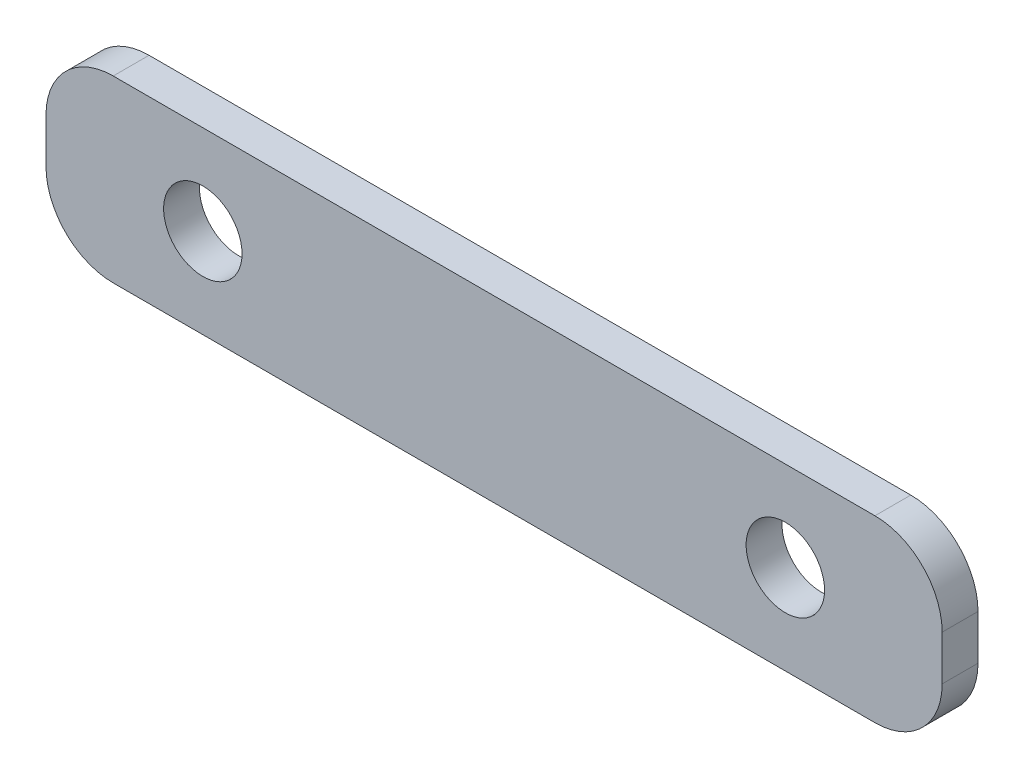
SolidWorks part; units mm, degrees
ref_plane "Plano frontal" through (0, 0, 0) normal (0, 0, 1) x (1, 0, 0)
ref_plane "Plano superior" through (0, 0, 0) normal (0, 1, 0) x (1, 0, 0)
ref_plane "Plano direito" through (0, 0, 0) normal (1, 0, 0) x (0, 0, -1)
sketch "Esboço1" plane through (0, 0, 0) normal (0, 0, 1) x (1, 0, 0)
  line L0 (0, 0) -> (0, 40)
  line L1 (0, 40) -> (200, 40)
  line L2 (200, 40) -> (200, 0)
  line L3 (200, 0) -> (0, 0)
  dimension "D1" = 40
  dimension "D2" = 200
extrude "Ressalto-extrusão1" add sketch "Esboço1" along normal mid plane 8
fillet "Filete2" radius 15 4 edges at (200, 0, 0) (200, 40, 0) (0, 0, 0) (0, 40, 0)
hole_wizard "Broca de rosquear para tarraxa de M201" positions "Esboço7" profile "Esboço6" hole size "M20" standard "DIN" end condition through all
sketch "Esboço7" plane through (0, 0, 4) normal (0, 0, 1) x (1, 0, 0)
  line L5 (0, 25) -> (0, 15) construction
  line L6 (200, 15) -> (200, 25) construction
  point P2 (35, 20)
  point P9 (165, 20)
  dimension "D1" = 35
  dimension "D2" = 35
sketch "Esboço6" plane through (35, 20, 4) normal (1, 0, 0) x (0, -1, 0)
  line L0 (0, 0) -> (0, 8)
  line L1 (0, 8) -> (8.75, 8)
  line L2 (8.75, 8) -> (8.75, 0)
  line L5 (8.75, 0) -> (0, 0)
  line L11 (0, -6.35) -> (0, 107.95) construction
  dimension "Thru Hole Dia." = 17.5
  dimension "Thru Hole Depth" = 8
